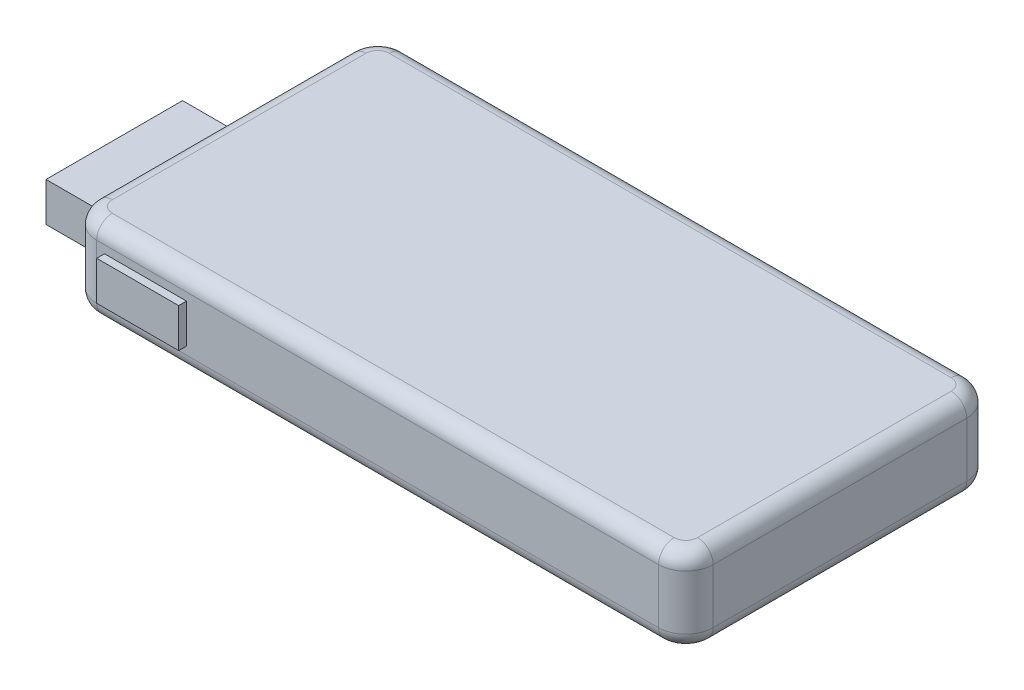
SolidWorks part; units mm, degrees
material "PE High Density"
ref_plane "Front Plane" through (0, 0, 0) normal (0, 0, 1) x (1, 0, 0)
ref_plane "Top Plane" through (0, 0, 0) normal (0, 1, 0) x (1, 0, 0)
ref_plane "Right Plane" through (0, 0, 0) normal (1, 0, 0) x (0, 0, -1)
sketch "Sketch1" plane through (0, 0, 0) normal (0, 1, 0) x (1, 0, 0)
  line L1 (-142.4796, 4.6531) -> (1.5204, 4.6531)
  line L2 (-149.4796, -2.3469) -> (-149.4796, -67.3469)
  line L3 (-142.4796, -74.3469) -> (1.5204, -74.3469)
  line L4 (8.5204, -2.3469) -> (8.5204, -67.3469)
  arc A0 (-149.4796, -67.3469) -> (-142.4796, -74.3469) centre (-142.4796, -67.3469) ccw
  arc A1 (1.5204, -74.3469) -> (8.5204, -67.3469) centre (1.5204, -67.3469) ccw
  arc A2 (1.5204, 4.6531) -> (8.5204, -2.3469) centre (1.5204, -2.3469) cw
  arc A3 (-142.4796, 4.6531) -> (-149.4796, -2.3469) centre (-142.4796, -2.3469) ccw
  point P8 (8.5204, -74.3469)
  point P11 (8.5204, 4.6531)
  point P14 (-149.4796, 4.6531)
  dimension "D3" = 7
  dimension "D1" = 158
  dimension "D2" = 79
extrude "Boss-Extrude1" add sketch "Sketch1" along normal blind 22
fillet "Fillet1" radius 4 8 edges at (-149.4796, 22, 34.8469) (-147.4293, 22, -2.6029) (-70.4796, 22, -4.6531) (6.4702, 22, -2.6029) (8.5204, 22, 34.8469) (6.4702, 22, 72.2966) (-70.4796, 22, 74.3469) (-147.4293, 22, 72.2966)
fillet "Fillet2" radius 4 8 edges at (-70.4796, 0, 74.3469) (6.4702, 0, 72.2966) (8.5204, 0, 34.8469) (6.4702, 0, -2.6029) (-70.4796, 0, -4.6531) (-147.4293, 0, -2.6029) (-149.4796, 0, 34.8469) (-147.4293, 0, 72.2966)
sketch "Sketch3" plane through (-149.4796, 0, 0) normal (-1, 0, 0) x (0, 0, 1)
  line L0 (-4.6531, 18) -> (-4.6531, 4) construction
  line L1 (65.3469, 16) -> (30.3469, 16)
  line L2 (65.3469, 16) -> (65.3469, 6)
  line L3 (65.3469, 6) -> (30.3469, 6)
  line L4 (30.3469, 16) -> (30.3469, 6)
  line L5 (67.3469, 18) -> (2.3469, 18) construction
  line L6 (2.3469, 4) -> (67.3469, 4) construction
  line L7 (67.3469, 18) -> (67.3469, 4) construction
  dimension "D1" = 35
  dimension "D2" = 2
  dimension "D3" = 2
  dimension "D4" = 2
extrude "Boss-Extrude3" add sketch "Sketch3" along normal blind 15
sketch "Sketch4" plane through (0, 0, 74.3469) normal (0, 0, 1) x (1, 0, 0)
  line L0 (-142.4796, 18) -> (-142.4796, 4) construction
  line L1 (-142.4796, 4) -> (1.5204, 4) construction
  text T0 "VARTA 20000mAh Battery Pack\r\n" font "Century Gothic" height 5
  dimension "D1" = 28
  dimension "D2" = 4
extrude "Boss-Extrude4" add sketch "Sketch4" against normal blind 1 separate body
sketch "Sketch5" plane through (0, 0, 74.3469) normal (0, 0, 1) x (1, 0, 0)
  line L0 (1.5204, 18) -> (-142.4796, 18) construction
  line L1 (-140.4796, 16) -> (-119.4796, 16)
  line L2 (-140.4796, 16) -> (-140.4796, 6)
  line L3 (-140.4796, 6) -> (-119.4796, 6)
  line L4 (-119.4796, 16) -> (-119.4796, 6)
  line L5 (-142.4796, 4) -> (1.5204, 4) construction
  line L6 (-142.4796, 18) -> (-142.4796, 4) construction
  line L7 (-149.4796, 6) -> (-149.4796, 16) construction
  dimension "D1" = 2
  dimension "D2" = 2
  dimension "D3" = 2
  dimension "D4" = 30
extrude "Boss-Extrude5" add sketch "Sketch5" along normal blind 2
